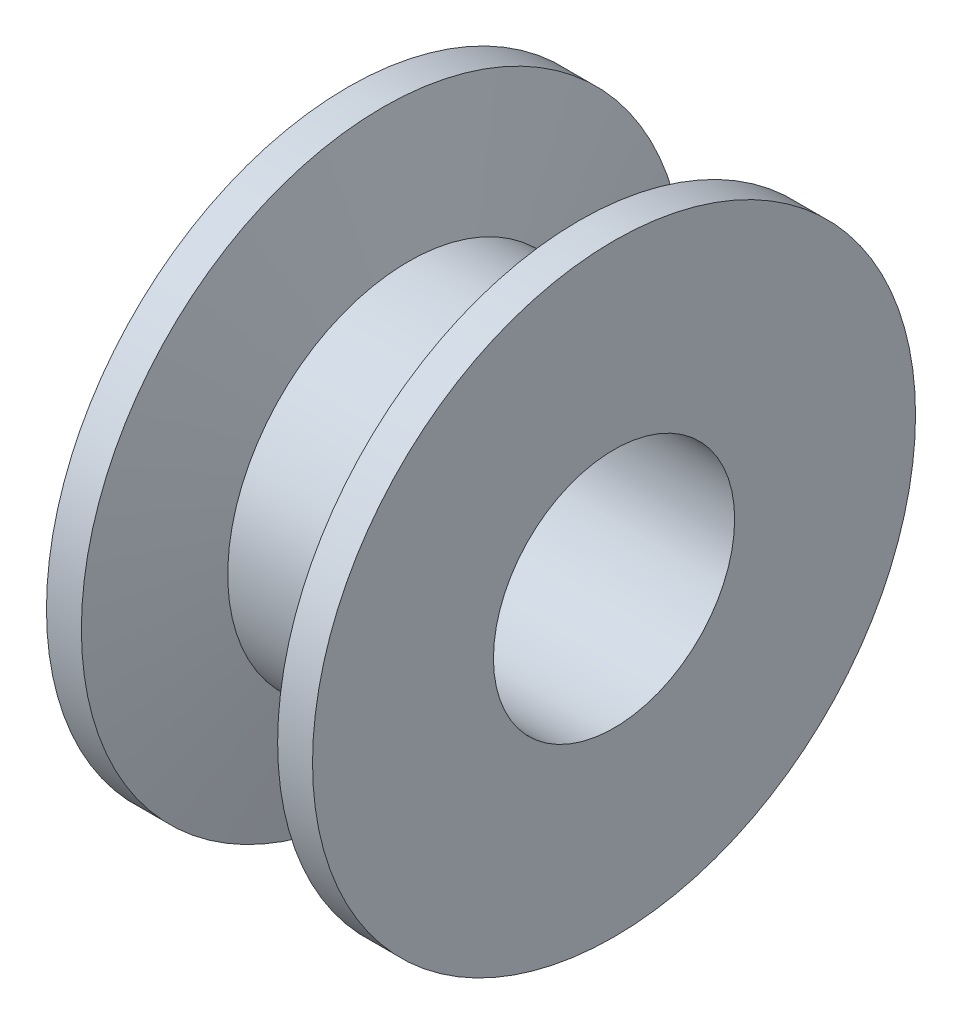
SolidWorks part; units mm, degrees
ref_plane "Front Plane" through (0, 0, 0) normal (0, 0, 1) x (1, 0, 0)
ref_plane "Top Plane" through (0, 0, 0) normal (0, 1, 0) x (1, 0, 0)
ref_plane "Right Plane" through (0, 0, 0) normal (1, 0, 0) x (0, 0, -1)
sketch "Sketch1" plane through (0, 0, 0) normal (0, 0, 1) x (1, 0, 0)
  line L1 (-6, 15) -> (6, 15)
  line L2 (6, 15) -> (8.1366, 25)
  line L3 (-11.0315, 25) -> (-11.0315, 10)
  line L4 (-8.1366, 25) -> (-11.0315, 25)
  line L5 (8.1366, 25) -> (11.0315, 25)
  line L6 (-6, 15) -> (-8.1366, 25)
  line L7 (-11.0315, 10) -> (11.0315, 10)
  line L8 (11.0315, 25) -> (11.0315, 10)
  line L9 (11.0315, 0) -> (-11.0315, 0) construction
  dimension "D2" = 25
  dimension "D3" = 10
revolve "Revolve3" add sketch "Sketch1" angle 360 about L9
